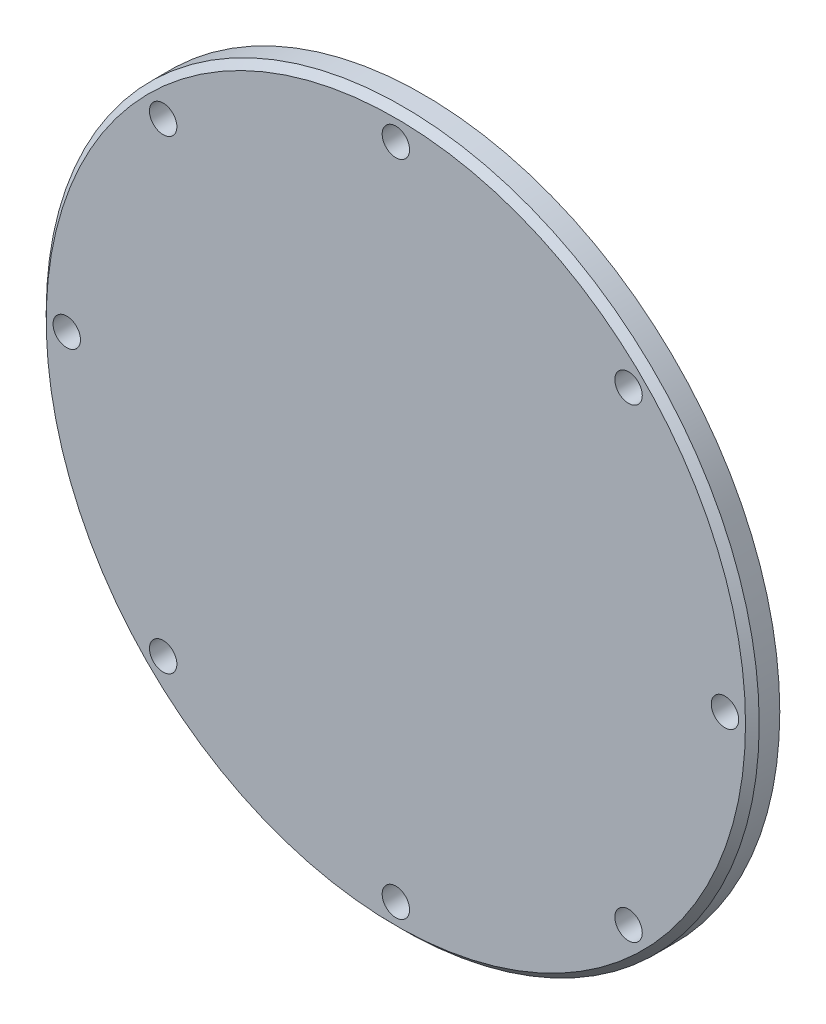
SolidWorks part; units mm, degrees
ref_plane "Спереди" through (0, 0, 0) normal (0, 0, 1) x (1, 0, 0)
ref_plane "Сверху" through (0, 0, 0) normal (0, 1, 0) x (1, 0, 0)
ref_plane "Справа" through (0, 0, 0) normal (1, 0, 0) x (0, 0, -1)
sketch "Эскиз1" plane through (0, 0, 0) normal (0, 0, 1) x (1, 0, 0)
  circle A0 centre (0, 0) radius 26
  dimension "D1" = 52
extrude "Бобышка-Вытянуть1" add sketch "Эскиз1" along normal blind 2
sketch "Эскиз2" plane through (0, 0, 2) normal (0, 0, 1) x (1, 0, 0)
  line L0 (0, 26) -> (0, -26) construction
  line L1 (-26, 0) -> (26, 0) construction
  circle A0 centre (0, 0) radius 24 construction
  circle A1 centre (0, 0) radius 26 construction
  circle A2 centre (0, 24) radius 1
  circle A3 centre (16.9706, 16.9706) radius 1
  circle A4 centre (24, 0) radius 1
  circle A5 centre (16.9706, -16.9706) radius 1
  circle A6 centre (0, -24) radius 1
  circle A7 centre (-16.9706, -16.9706) radius 1
  circle A8 centre (-24, 0) radius 1
  circle A9 centre (-16.9706, 16.9706) radius 1
  point P28 (0, 0)
  dimension "D1" = 48
  dimension "D2" = 2
  dimension "D3" = 8
extrude "Вырез-Вытянуть1" cut sketch "Эскиз2" against normal blind 2
chamfer "Фаска2" distance 0.5 angle 45 1 edges at (26, 0, 2)
